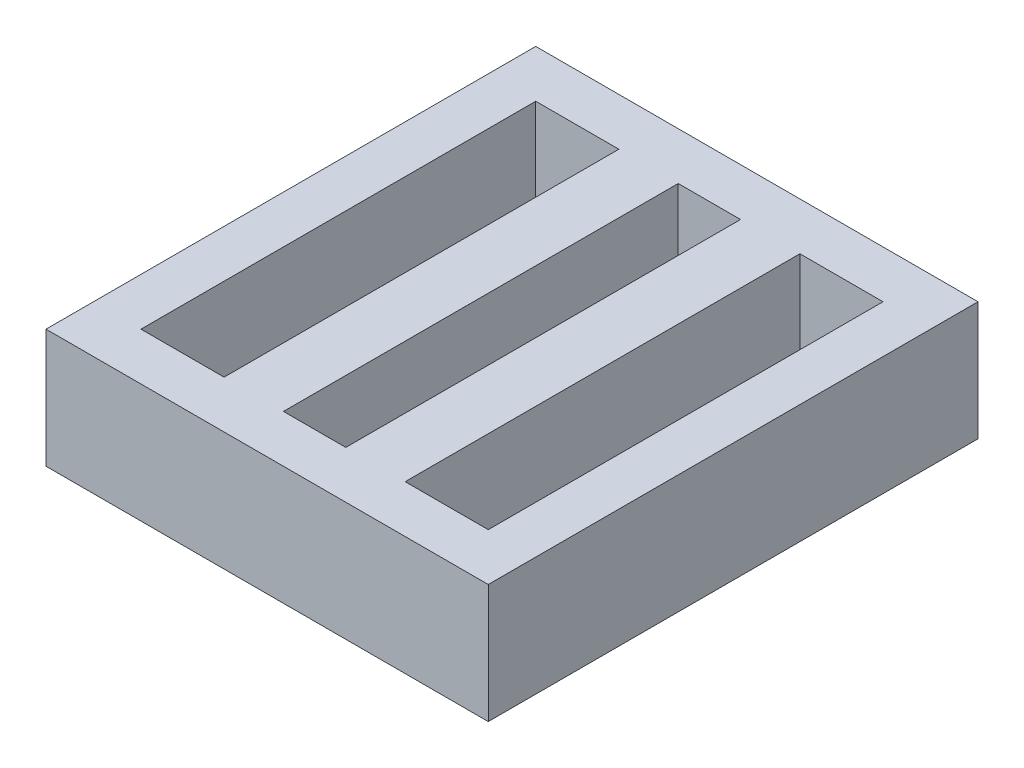
SolidWorks part; units mm, degrees
ref_plane "Front Plane" through (0, 0, 0) normal (0, 0, 1) x (1, 0, 0)
ref_plane "Top Plane" through (0, 0, 0) normal (0, 1, 0) x (1, 0, 0)
ref_plane "Right Plane" through (0, 0, 0) normal (1, 0, 0) x (0, 0, -1)
sketch "Sketch1" plane through (0, 0, 0) normal (0, 1, 0) x (1, 0, 0)
  line L0 (-292.5, 332.5) -> (-292.5, -332.5)
  line L1 (372.5, 412.5) -> (-372.5, 412.5)
  line L2 (372.5, 412.5) -> (372.5, -412.5)
  line L3 (372.5, -412.5) -> (-372.5, -412.5)
  line L4 (-372.5, 412.5) -> (-372.5, -412.5)
  line L5 (372.5, 412.5) -> (-372.5, -412.5) construction
  line L6 (372.5, -412.5) -> (-372.5, 412.5) construction
  line L7 (292.5, -332.5) -> (152.5, -332.5)
  line L8 (292.5, 332.5) -> (292.5, -332.5)
  line L9 (292.5, 332.5) -> (152.5, 332.5)
  line L10 (-152.5, -332.5) -> (-152.5, 332.5)
  line L11 (-52.5, 332.5) -> (-52.5, -332.5)
  line L12 (52.5, 332.5) -> (52.5, -332.5)
  line L13 (152.5, -332.5) -> (152.5, 332.5)
  line L14 (-152.5, 332.5) -> (-292.5, 332.5)
  line L15 (52.5, 332.5) -> (-52.5, 332.5)
  line L16 (292.5, 332.5) -> (-292.5, 332.5) construction
  line L17 (52.5, -332.5) -> (-52.5, -332.5)
  line L18 (-152.5, -332.5) -> (-292.5, -332.5)
  line L19 (292.5, -332.5) -> (-292.5, -332.5) construction
  point P0 (0, 0)
  dimension "D1" = 745
  dimension "D2" = 825
  dimension "D4" = 665
  dimension "D5" = 665
  dimension "D6" = 665
  dimension "D7" = 665
  dimension "D8" = 100
  dimension "D9" = 100
  dimension "D10" = 140
  dimension "D11" = 140
  dimension "D3" = 80
extrude "Boss-Extrude1" add sketch "Sketch1" along normal blind 200
